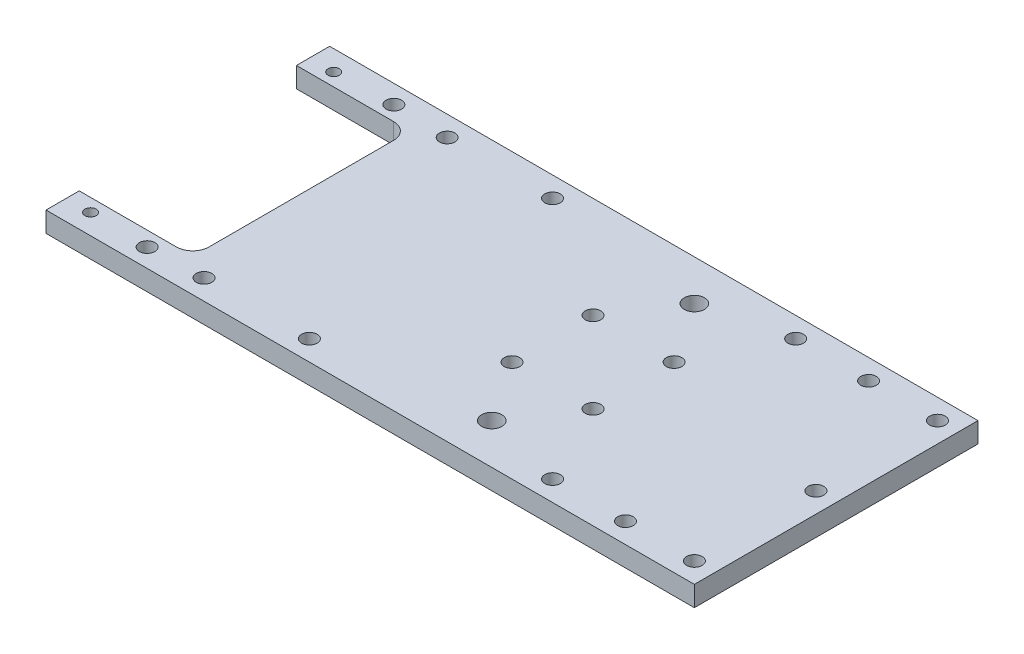
SolidWorks part; units mm, degrees
ref_plane "Front Plane" through (0, 0, 0) normal (0, 0, 1) x (1, 0, 0)
ref_plane "Top Plane" through (0, 0, 0) normal (0, 1, 0) x (1, 0, 0)
ref_plane "Right Plane" through (0, 0, 0) normal (1, 0, 0) x (0, 0, -1)
sketch "Sketch1" plane through (0, 0, 0) normal (0, 1, 0) x (1, 0, 0)
  line L1 (-50.8, -22.225) -> (50.8, -22.225)
  line L2 (-50.8, -22.225) -> (-50.8, 22.225)
  line L3 (-50.8, 22.225) -> (50.8, 22.225)
  line L4 (50.8, -22.225) -> (50.8, 22.225)
  line L5 (-50.8, -22.225) -> (50.8, 22.225) construction
  line L6 (-50.8, 22.225) -> (50.8, -22.225) construction
  point P0 (0, 0)
  dimension "D1" = 44.45
  dimension "D2" = 101.6
extrude "Boss-Extrude1" add sketch "Sketch1" along normal blind 3.175
sketch "Sketch2" plane through (0, 3.175, 0) normal (0, 1, 0) x (1, 0, 0)
  line L0 (-50.8, 0) -> (50.8, 0) construction
  line L1 (-50.8, 22.225) -> (-50.8, -22.225) construction
  line L2 (50.8, -22.225) -> (50.8, 22.225) construction
  line L3 (50.8, 19.05) -> (-50.8, 19.05) construction
  line L4 (50.8, -19.05) -> (-50.8, -19.05) construction
  line L5 (-50.8, -6.35) -> (50.8, -6.35) construction
  line L6 (-50.8, 6.35) -> (50.8, 6.35) construction
  circle A0 centre (-46.99, 19.05) radius 0.889
  circle A1 centre (-29.21, 19.05) radius 1.2192
  circle A2 centre (-12.7, 19.05) radius 1.2192
  circle A3 centre (25.4, 19.05) radius 1.2192
  circle A4 centre (36.83, 19.05) radius 1.2192
  circle A5 centre (47.625, 19.05) radius 1.2192
  circle A6 centre (47.625, 0) radius 1.2192
  circle A7 centre (47.625, -19.05) radius 1.2192
  circle A8 centre (36.83, -19.05) radius 1.2192
  circle A9 centre (25.4, -19.05) radius 1.2192
  circle A10 centre (-12.7, -19.05) radius 1.2192
  circle A11 centre (-29.21, -19.05) radius 1.2192
  circle A12 centre (-46.99, -19.05) radius 0.889
  circle A13 centre (19.05, -6.35) radius 1.2192
  circle A14 centre (19.05, 6.35) radius 1.2192
  circle A15 centre (6.35, 6.35) radius 1.2192
  circle A16 centre (6.35, -6.35) radius 1.2192
  dimension "D3" = 1.778
  dimension "D4" = 2.4384
  dimension "D5" = 2.4384
  dimension "D6" = 2.4384
  dimension "D7" = 2.4384
  dimension "D8" = 2.4384
  dimension "D9" = 2.4384
  dimension "D10" = 2.4384
  dimension "D11" = 2.4384
  dimension "D12" = 2.4384
  dimension "D13" = 2.4384
  dimension "D14" = 2.4384
  dimension "D15" = 1.778
  dimension "D18" = 2.4384
  dimension "D19" = 2.4384
  dimension "D20" = 2.4384
  dimension "D21" = 2.4384
  dimension "D1" = 19.05
  dimension "D2" = 19.05
  dimension "D16" = 6.35
  dimension "D17" = 6.35
  dimension "D22" = 3.81
  dimension "D23" = 21.59
  dimension "D24" = 38.1
  dimension "D25" = 57.15
  dimension "D26" = 69.85
  dimension "D27" = 76.2
  dimension "D28" = 87.63
  dimension "D29" = 98.425
extrude "Cut-Extrude1" cut sketch "Sketch2" against normal through all
sketch "Sketch3" plane through (0, 3.175, 0) normal (0, 1, 0) x (1, 0, 0)
  line L0 (-50.8, 0) -> (50.8, 0) construction
  line L1 (-50.8, 22.225) -> (-50.8, -22.225) construction
  line L2 (50.8, -22.225) -> (50.8, 22.225) construction
  circle A0 centre (-37.846, 19.3294) radius 1.2192
  circle A1 centre (12.7, 15.875) radius 1.5875
  dimension "D1" = 2.4384
  dimension "D2" = 3.175
  dimension "D3" = 63.5
  dimension "D4" = 15.875
  dimension "D5" = 12.954
  dimension "D6" = 19.3294
extrude "Cut-Extrude2" cut sketch "Sketch3" against normal through all
mirror "Mirror1" about plane through (0, 0, 0) normal (0, 0, 1) of "Cut-Extrude2"
sketch "Sketch4" plane through (0, 3.175, 0) normal (0, 1, 0) x (1, 0, 0)
  line L0 (-50.8, 22.225) -> (-50.8, -22.225) construction
  line L1 (-33.02, -17.018) -> (-50.8, -17.018)
  line L2 (-33.02, -17.018) -> (-33.02, 17.018)
  line L3 (-33.02, 17.018) -> (-50.8, 17.018)
  line L4 (-50.8, -17.018) -> (-50.8, 17.018)
  line L5 (-33.02, -17.018) -> (-50.8, 17.018) construction
  line L6 (-33.02, 17.018) -> (-50.8, -17.018) construction
  point P0 (-41.91, 0)
  dimension "D1" = 17.78
  dimension "D2" = 34.036
extrude "Cut-Extrude3" cut sketch "Sketch4" against normal through all
fillet "Fillet2" radius 2.54 2 edges at (-33.02, 1.5875, 17.018) (-33.02, 1.5875, -17.018)
